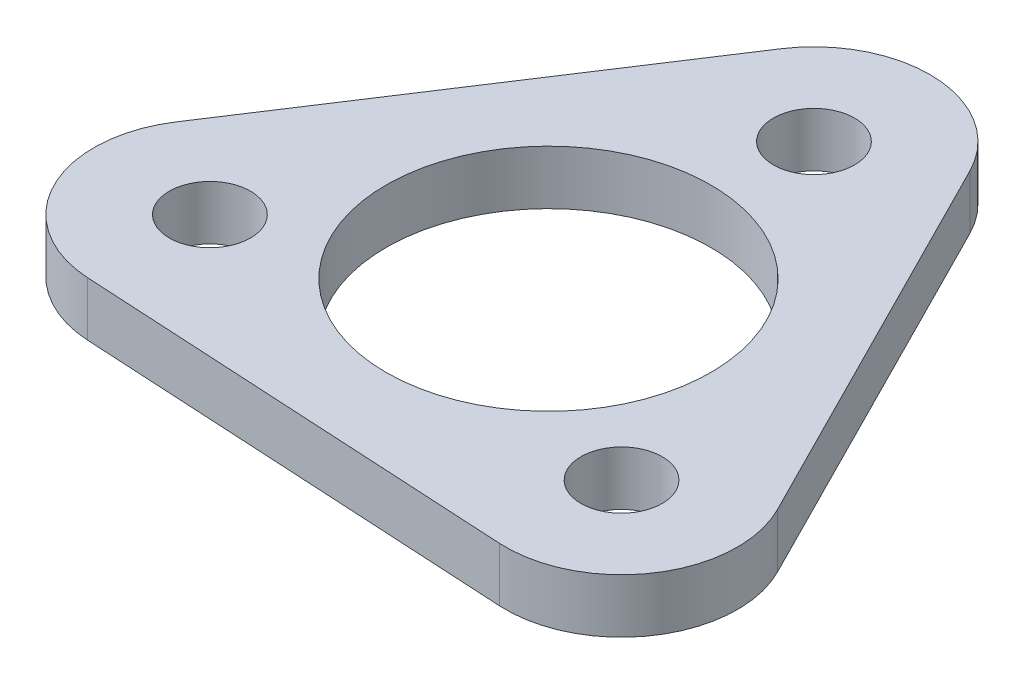
SolidWorks part; units mm, degrees
ref_plane "Alzado" through (0, 0, 0) normal (0, 0, 1) x (1, 0, 0)
ref_plane "Planta" through (0, 0, 0) normal (0, 1, 0) x (1, 0, 0)
ref_plane "Vista lateral" through (0, 0, 0) normal (1, 0, 0) x (0, 0, -1)
sketch "Croquis1" plane through (0, 0, 0) normal (0, 1, 0) x (1, 0, 0)
  line L1 (-0.8544, -0.8482) -> (0.7556, -0.9372)
  line L2 (1.1617, -0.3158) -> (0.4338, 1.123)
  line L3 (-0.3074, 1.164) -> (-1.1895, -0.1858)
  circle A0 centre (0, 0) radius 0.8941 construction
  circle A1 centre (0, 0) radius 0.6
  arc A2 (-0.8544, -0.8482) -> (-1.1895, -0.1858) centre (-0.8307, -0.4203) cw
  arc A3 (0.7556, -0.9372) -> (1.1617, -0.3158) centre (0.7793, -0.5093) ccw
  arc A4 (0.4338, 1.123) -> (-0.3074, 1.164) centre (0.0514, 0.9295) ccw
  circle A5 centre (0.0514, 0.9295) radius 0.15
  circle A6 centre (0.7793, -0.5093) radius 0.15
  circle A7 centre (-0.8307, -0.4203) radius 0.15
  dimension "D1" = 0.3
  dimension "D2" = 1.2
  dimension "D3" = 0.3
  dimension "D4" = 1.61
  dimension "D5" = 0.3
extrude "Saliente-Extruir1" add sketch "Croquis1" along normal blind 0.2 contours A4 L3 A2 L1 A3 L2 | A1 | A7 | A6 | A5
